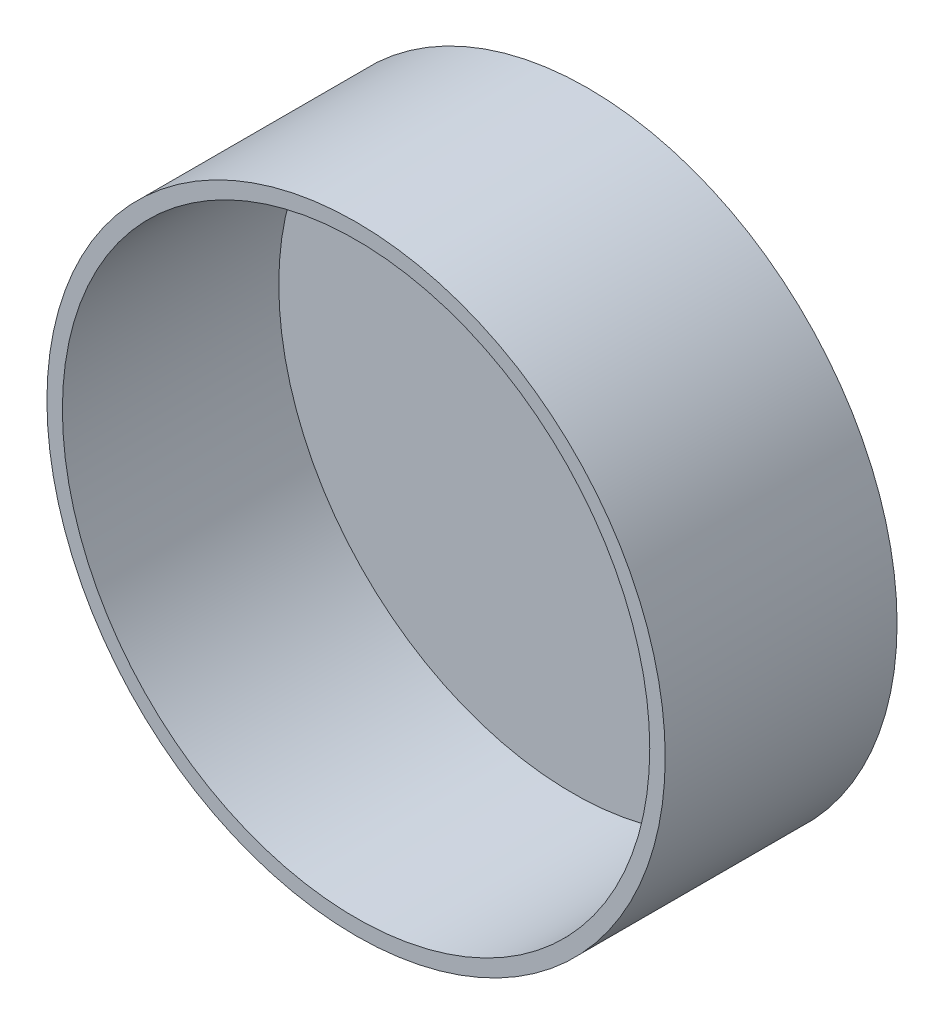
SolidWorks part; units mm, degrees
ref_plane "前视基准面" through (0, 0, 0) normal (0, 0, 1) x (1, 0, 0)
ref_plane "上视基准面" through (0, 0, 0) normal (0, 1, 0) x (1, 0, 0)
ref_plane "右视基准面" through (0, 0, 0) normal (1, 0, 0) x (0, 0, -1)
sketch "草图1" plane through (0, 0, 0) normal (0, 0, 1) x (1, 0, 0)
  circle A0 centre (0, 0) radius 100
  circle A1 centre (0, 0) radius 95
  dimension "D1" = 200
  dimension "D2" = 5
extrude "凸台-拉伸1" add sketch "草图1" along normal blind 70
sketch "草图2" plane through (0, 0, 0) normal (0, 0, -1) x (-1, 0, 0)
  circle A1 centre (0, 0) radius 100
  circle A2 centre (0, 0) radius 100
  dimension "D1" = 0
extrude "凸台-拉伸2" add sketch "草图2" along normal blind 5
